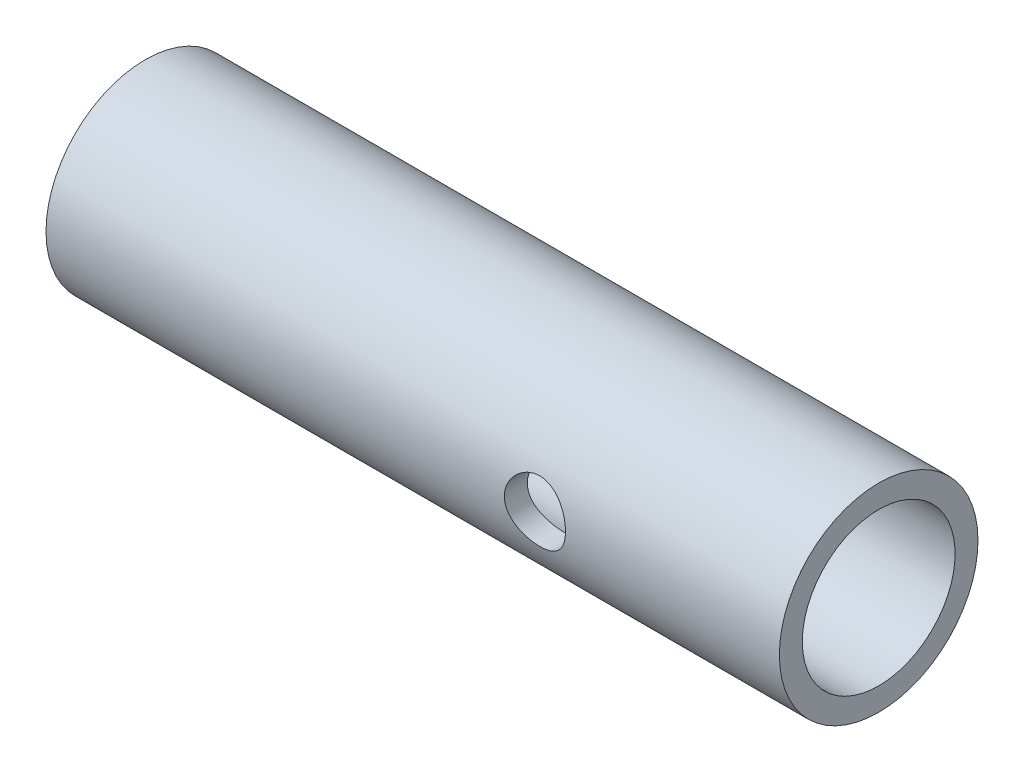
SolidWorks part; units mm, degrees
material "Plain Carbon Steel"
ref_plane "Front Plane" through (0, 0, 0) normal (0, 0, 1) x (1, 0, 0)
ref_plane "Top Plane" through (0, 0, 0) normal (0, 1, 0) x (1, 0, 0)
ref_plane "Right Plane" through (0, 0, 0) normal (1, 0, 0) x (0, 0, -1)
sketch "Sketch1" plane through (0, 0, 0) normal (0, 0, 1) x (1, 0, 0)
  line L0 (0, 15.875) -> (152.4, 15.875)
  line L1 (152.4, 15.875) -> (152.4, 20.6375)
  line L2 (152.4, 20.6375) -> (0, 20.6375)
  line L3 (0, 20.6375) -> (0, 15.875)
  line L4 (0, 0) -> (171.2829, 0) construction
  dimension "D1" = 31.75
  dimension "D2" = 4.7625
  dimension "D3" = 152.4
revolve "Revolve1" add sketch "Sketch1" angle 360 about L4
sketch "Sketch2" plane through (0, 0, 0) normal (0, 0, 1) x (1, 0, 0)
  line L0 (152.4, -15.875) -> (152.4, 15.875) construction
  line L1 (101.6, 0) -> (0, 0) construction
  circle A0 centre (101.6, 0) radius 6.35
  dimension "D1" = 12.7
  dimension "D2" = 50.8
extrude "Cut-Extrude1" cut sketch "Sketch2" against normal through all and the other way through all
